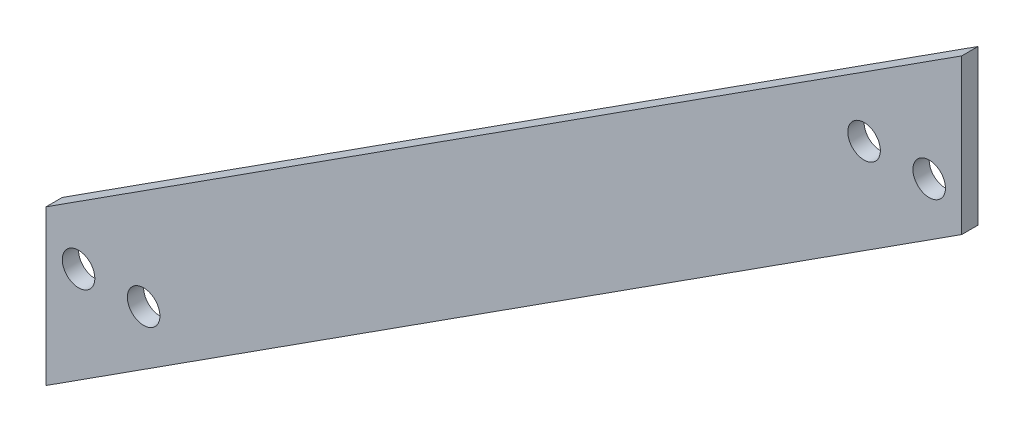
SolidWorks part; units mm, degrees
ref_plane "Front Plane" through (0, 0, 0) normal (0, 0, 1) x (1, 0, 0)
ref_plane "Top Plane" through (0, 0, 0) normal (0, 1, 0) x (1, 0, 0)
ref_plane "Right Plane" through (0, 0, 0) normal (1, 0, 0) x (0, 0, -1)
sketch "Sketch1" plane through (0, 0, 0) normal (0, 0, 1) x (1, 0, 0)
  line L0 (0, 0) -> (0, -45.2914)
  line L1 (0, -45.2914) -> (267.97, 126.946)
  line L2 (267.97, 126.946) -> (267.97, 172.2374)
  line L4 (267.97, 172.2374) -> (0, 0)
  line L5 (248.92, 129.8539) -> (267.97, 129.8539) construction
  line L6 (267.97, 172.2374) -> (288.5704, 140.1869) construction
  line L7 (288.5704, 140.1869) -> (267.97, 126.946) construction
  line L8 (0, 0) -> (-20.6004, -13.2409) construction
  line L9 (-20.6004, -13.2409) -> (0, -45.2914) construction
  circle A0 centre (9.525, -11.0014) radius 4.7625
  circle A1 centre (28.575, -11.0014) radius 4.7625
  circle A2 centre (239.395, 136.3186) radius 4.7625
  circle A3 centre (258.445, 136.3186) radius 4.7625
  point P16 (258.445, 129.8539)
  dimension "D5" = 9.525
  dimension "D9" = 9.525
  dimension "D1" = 38.1
  dimension "D2" = 147.32
  dimension "D3" = 267.97
  dimension "D6" = 19.05
  dimension "D7" = 9.525
  dimension "D8" = 34.29
  dimension "D10" = 19.05
  dimension "D11" = 9.3726
extrude "Boss-Extrude1" add sketch "Sketch1" along normal blind 4.7625
